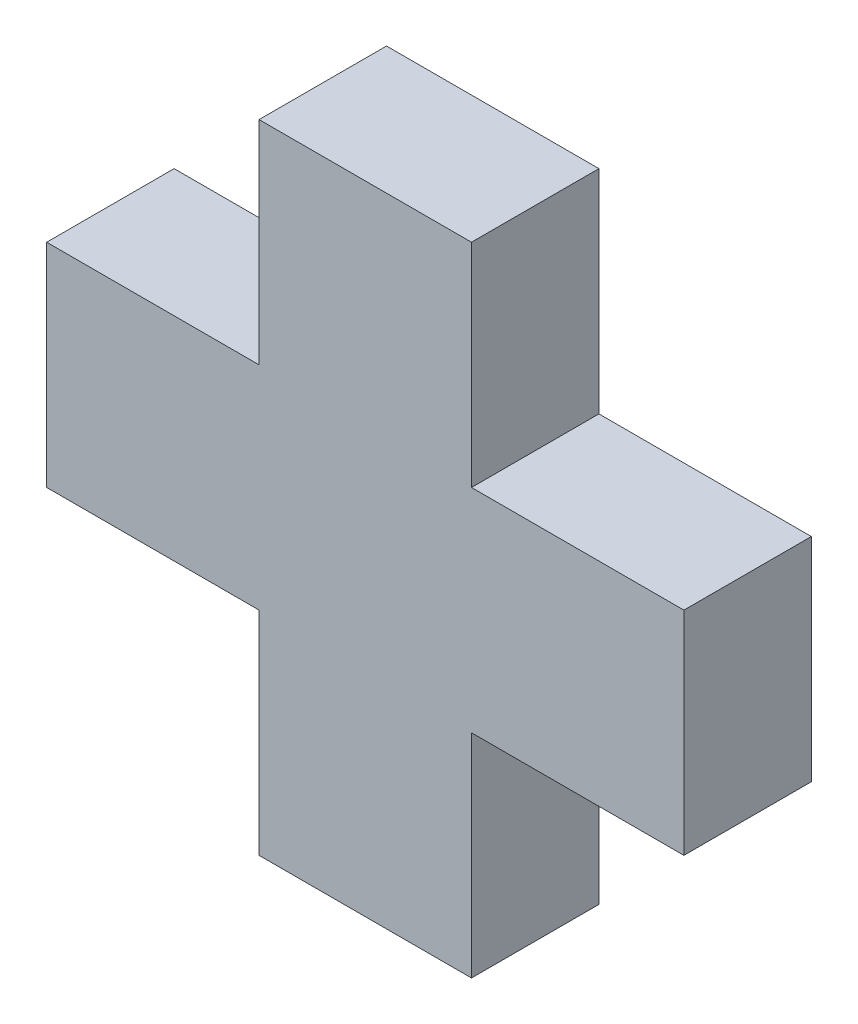
SolidWorks part; units mm, degrees
ref_plane "Ebene vorne" through (0, 0, 0) normal (0, 0, 1) x (1, 0, 0)
ref_plane "Ebene oben" through (0, 0, 0) normal (0, 1, 0) x (1, 0, 0)
ref_plane "Ebene rechts" through (0, 0, 0) normal (1, 0, 0) x (0, 0, -1)
sketch "Sketch1" plane through (0, 0, 0) normal (0, 0, 1) x (1, 0, 0)
  line L0 (-2.7546, 3.8657) -> (-2.7546, 0.5324)
  line L1 (-2.7546, 0.5324) -> (-6.088, 0.5324)
  line L2 (-6.088, 0.5324) -> (-6.088, -2.8009)
  line L3 (-6.088, -2.8009) -> (-2.7546, -2.8009)
  line L4 (-2.7546, -2.8009) -> (-2.7546, -6.1343)
  line L5 (-2.7546, -6.1343) -> (0.5787, -6.1343)
  line L6 (0.5787, -6.1343) -> (0.5787, -2.8009)
  line L7 (0.5787, -2.8009) -> (3.912, -2.8009)
  line L8 (3.912, -2.8009) -> (3.912, 0.5324)
  line L9 (3.912, 0.5324) -> (0.5787, 0.5324)
  line L10 (0.5787, 0.5324) -> (0.5787, 3.8657)
  line L11 (0.5787, 3.8657) -> (-2.7546, 3.8657)
  dimension "D1" = 10
extrude "Boss-Extrude1" add sketch "Sketch1" along normal blind 2
